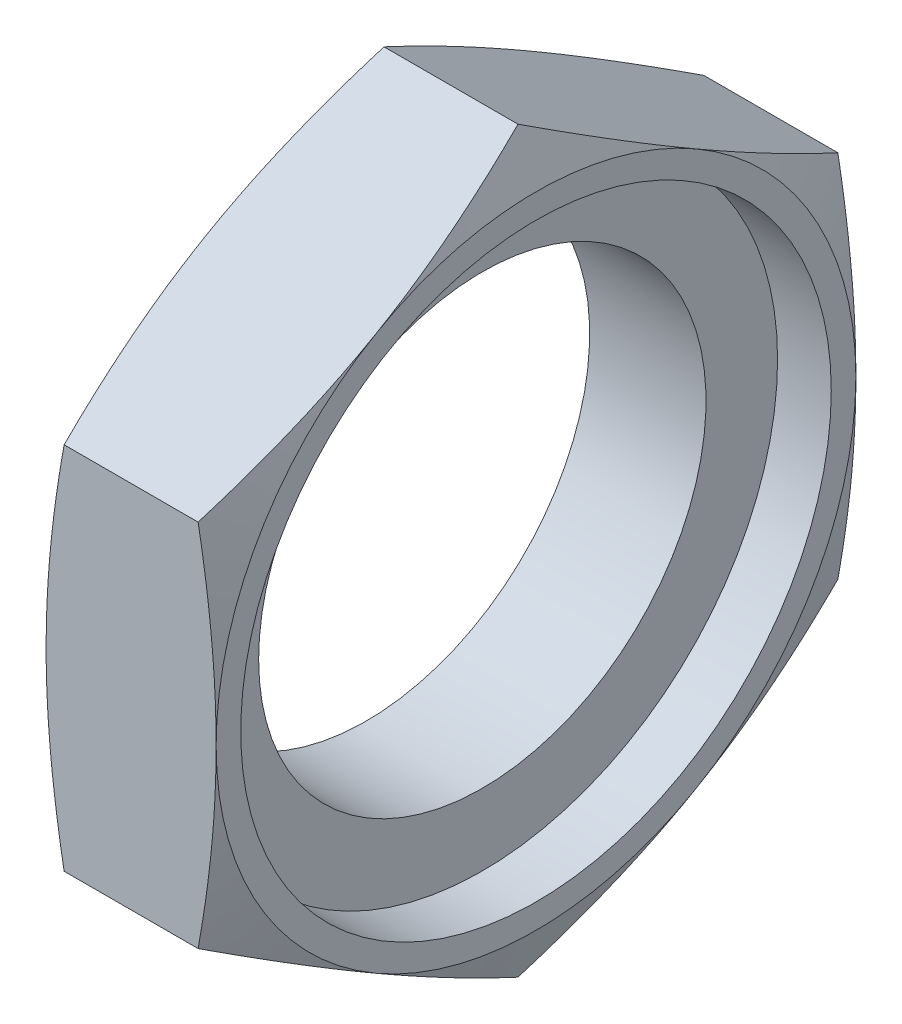
SolidWorks part; units mm, degrees
material "AISI 1020"
ref_plane "Plano superior" through (0, 0, 0) normal (0, 0, 1) x (1, 0, 0)
ref_plane "Plano frontal" through (0, 0, 0) normal (0, 1, 0) x (1, 0, 0)
ref_plane "Plano direito" through (0, 0, 0) normal (1, 0, 0) x (0, 0, -1)
sketch "Esboço1" plane through (0, 0, 0) normal (1, 0, 0) x (0, 0, -1)
  line L0 (14.3, 8.2561) -> (14.3, -8.2561)
  line L1 (14.3, 8.2561) -> (0, 16.5122)
  line L2 (0, 16.5122) -> (-14.3, 8.2561)
  line L3 (-14.3, 8.2561) -> (-14.3, -8.2561)
  line L4 (-14.3, -8.2561) -> (0, -16.5122)
  line L5 (0, -16.5122) -> (14.3, -8.2561)
  line L8 (14.3, -8.2561) -> (14.3, 8.2561) [skipped]
  circle A0 centre (0, 0) radius 14.3 construction
  circle A1 centre (0, 0) radius 10
  dimension "D1" = 28.6
  dimension "D2" = 20
extrude "Ressalto-extrusão1" add sketch "Esboço1" along normal blind 7.6
cosmetic thread "Representação de rosca2" parameters "D2"=22
sketch "Esboço3" plane through (0, 0, 0) normal (-1, 0, 0) x (0, 0, 1)
  circle A0 centre (0, 0) radius 14.3
sketch "Esboço4" plane through (7.6, 0, 0) normal (1, 0, 0) x (0, 0, -1)
  circle A0 centre (0, 0) radius 14.3
hole_wizard "Furo1" positions "Esboço5" profile "Esboço6" legacy
sketch "Esboço5" plane through (7.6, 0, 0) normal (1, 0, 0) x (0, 0, -1)
  point P0 (0, 0)
  point P3 (0, 0)
sketch "Esboço6" plane through (7.6, 0, 0) normal (0, 1, 0) x (0, 0, -1)
  line L0 (0, 0) -> (0, 2.4)
  line L1 (0, 2.4) -> (13.2, 2.4)
  line L2 (13.2, 2.4) -> (13.2, 0)
  line L3 (13.2, 0) -> (0, 0)
  line L4 (0, 110) -> (0, -10) construction
  dimension "Diameter" = 26.4
  dimension "Depth" = 2.4
sketch "Esboço7" plane through (7.6, 0, 0) normal (1, 0, 0) x (0, 0, -1)
  circle A0 centre (0, 0) radius 14.3
extrude "Corte-extrusão1" cut sketch "Esboço7" against normal blind 13 draft 70 flip side to cut
sketch "Esboço8" plane through (0, 0, 0) normal (-1, 0, 0) x (0, 0, 1)
  circle A0 centre (0, 0) radius 14.3
extrude "Corte-extrusão2" cut sketch "Esboço8" against normal blind 13 draft 70 flip side to cut
